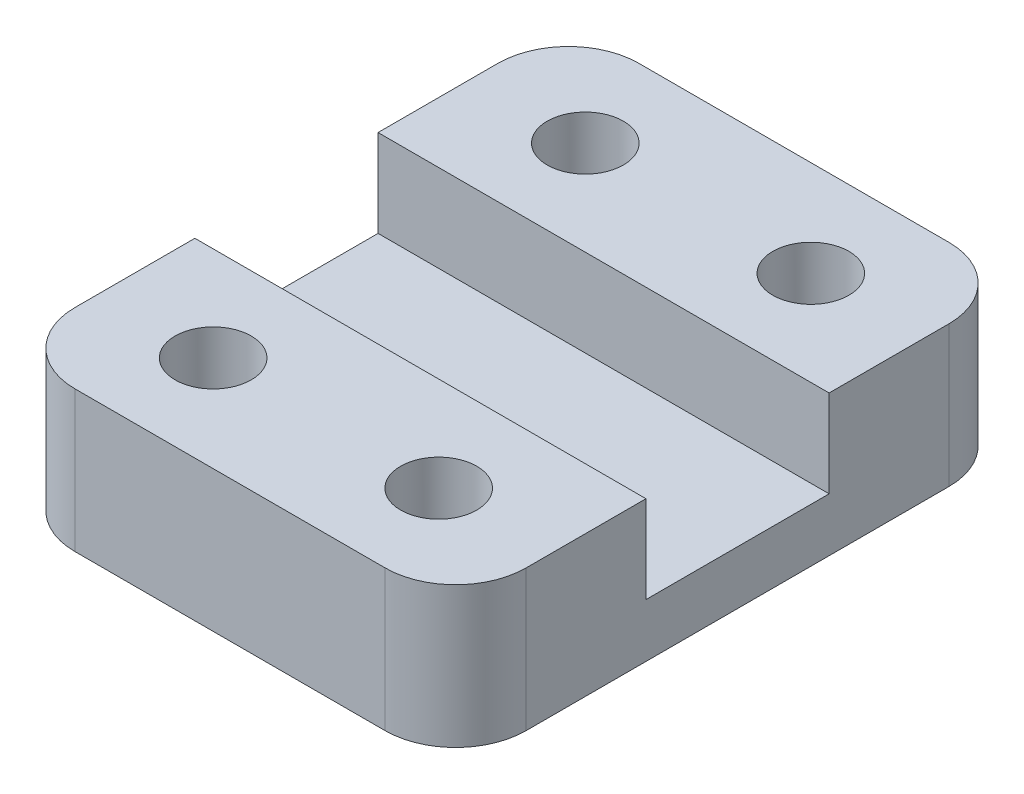
SolidWorks part; units mm, degrees
ref_plane "Front Plane" through (0, 0, 0) normal (0, 0, 1) x (1, 0, 0)
ref_plane "Top Plane" through (0, 0, 0) normal (0, 1, 0) x (1, 0, 0)
ref_plane "Right Plane" through (0, 0, 0) normal (1, 0, 0) x (0, 0, -1)
sketch "Sketch1" plane through (0, 0, 0) normal (0, 1, 0) x (1, 0, 0)
  line L1 (0, 0) -> (40.64, 0)
  line L2 (0, 0) -> (0, 50.8)
  line L3 (0, 50.8) -> (40.64, 50.8)
  line L4 (40.64, 0) -> (40.64, 50.8)
  dimension "D1" = 50.8
  dimension "D2" = 40.64
extrude "Boss-Extrude1" add sketch "Sketch1" along normal blind 12.7
sketch "Sketch3" plane through (40.64, 0, 0) normal (1, 0, 0) x (0, 0, -1)
  line L0 (25.4, 12.7) -> (25.4, 0) construction
  line L1 (0, 12.7) -> (50.8, 12.7) construction
  line L2 (0, 0) -> (50.8, 0) construction
  line L3 (17.149, 4.83) -> (33.651, 4.83)
  line L4 (17.399, 12.7) -> (33.401, 12.7) construction
  line L5 (17.399, 12.7) -> (17.399, 5.08) construction
  line L6 (17.399, 5.08) -> (33.401, 5.08) construction
  line L7 (33.401, 12.7) -> (33.401, 5.08) construction
  line L8 (33.651, 12.95) -> (33.651, 4.83)
  line L9 (17.149, 12.95) -> (33.651, 12.95)
  line L10 (17.149, 12.95) -> (17.149, 4.83)
  point P10 (25.4, 5.08)
  dimension "D1" = 0
  dimension "D2" = 16.002
  dimension "D3" = 7.62
  dimension "D4" = 0.25
extrude "Cut-Extrude1" cut sketch "Sketch3" against normal through all both and the other way through all
sketch "Sketch5" plane through (0, 12.7, 0) normal (0, 1, 0) x (1, 0, 0)
  line L0 (10.16, 0) -> (10.16, 50.8) construction
  line L1 (0, 0) -> (40.64, 0) construction
  line L2 (40.64, 50.8) -> (0, 50.8) construction
  line L3 (30.48, 50.8) -> (30.48, 0) construction
  line L4 (0, 50.8) -> (0, 33.651) construction
  line L5 (40.64, 33.651) -> (40.64, 50.8) construction
  line L6 (20.32, 0) -> (20.32, 50.8) construction
  line L7 (0, 8.636) -> (40.64, 8.636) construction
  line L8 (0, 17.149) -> (0, 0) construction
  line L9 (40.64, 0) -> (40.64, 17.149) construction
  line L10 (40.64, 42.164) -> (0, 42.164) construction
  circle A0 centre (10.16, 8.636) radius 3.429
  circle A1 centre (30.48, 8.636) radius 3.429
  circle A2 centre (30.48, 42.164) radius 3.429
  circle A3 centre (10.16, 42.164) radius 3.429
  dimension "D5" = 6.858
  dimension "D1" = 10.16
  dimension "D2" = 10.16
  dimension "D3" = 8.636
  dimension "D4" = 8.636
  dimension "D6" = 2
  dimension "D7" = 2
extrude "Cut-Extrude2" cut sketch "Sketch5" against normal through all both and the other way through all
fillet "Fillet1" radius 6.35 4 edges at (0, 6.35, 0) (0, 6.35, -50.8) (40.64, 6.35, -50.8) (40.64, 6.35, 0)
